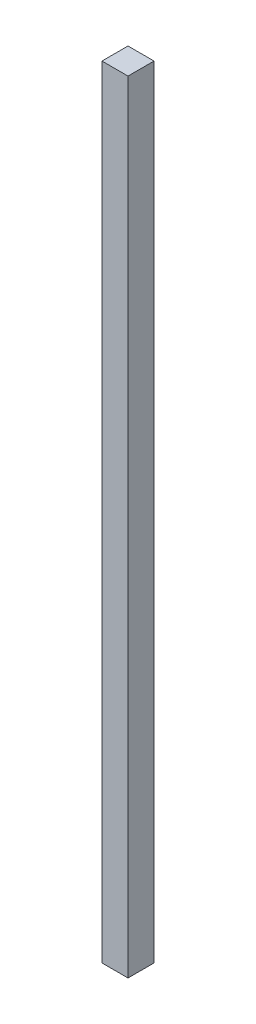
SolidWorks part; units mm, degrees
ref_plane "Front Plane" through (0, 0, 0) normal (0, 0, 1) x (1, 0, 0)
ref_plane "Top Plane" through (0, 0, 0) normal (0, 1, 0) x (1, 0, 0)
ref_plane "Right Plane" through (0, 0, 0) normal (1, 0, 0) x (0, 0, -1)
sketch "Sketch1" plane through (0, 0, 0) normal (0, 1, 0) x (1, 0, 0)
  line L1 (-10, 10) -> (10, 10)
  line L2 (-10, 10) -> (-10, -10)
  line L3 (-10, -10) -> (10, -10)
  line L4 (10, 10) -> (10, -10)
  line L5 (-10, 10) -> (10, -10) construction
  line L6 (-10, -10) -> (10, 10) construction
  point P0 (0, 0)
  dimension "D1" = 20
  dimension "D2" = 20
extrude "Boss-Extrude1" add sketch "Sketch1" along normal blind 600
